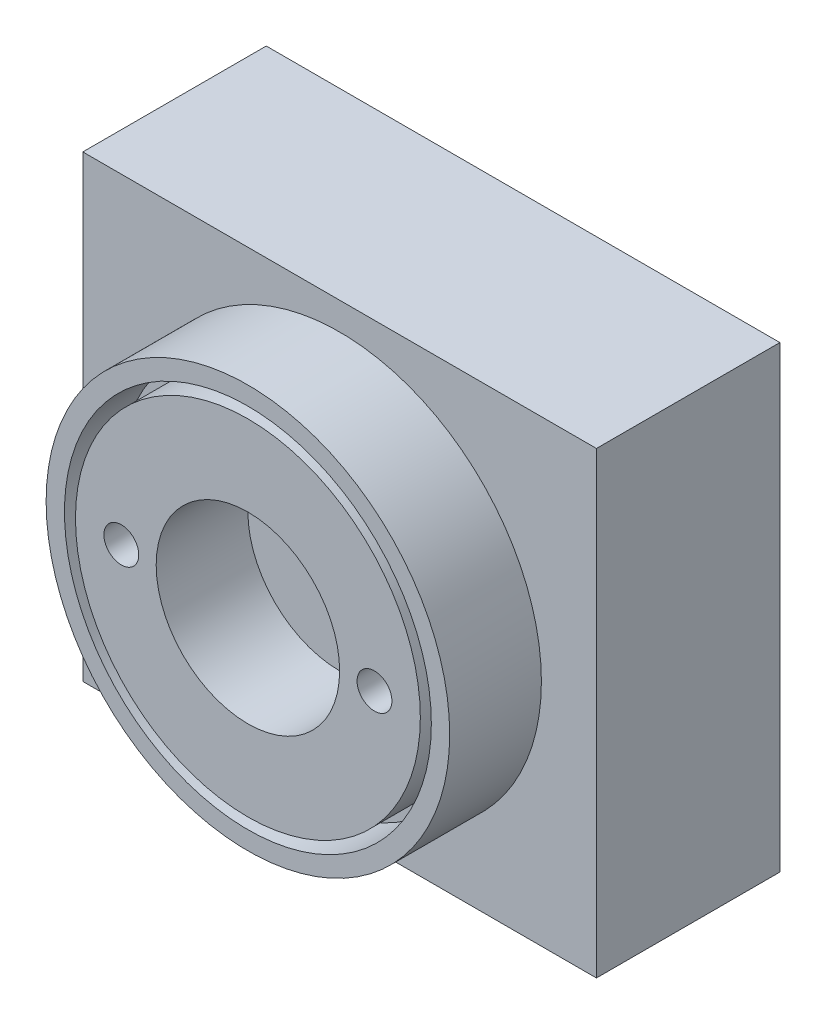
SolidWorks part; units mm, degrees
ref_plane "Front Plane" through (0, 0, 0) normal (0, 0, 1) x (1, 0, 0)
ref_plane "Top Plane" through (0, 0, 0) normal (0, 1, 0) x (1, 0, 0)
ref_plane "Right Plane" through (0, 0, 0) normal (1, 0, 0) x (0, 0, -1)
sketch "Sketch1" plane through (0, 0, 0) normal (0, 0, 1) x (1, 0, 0)
  circle A0 centre (0, 0) radius 55
  circle A1 centre (0, 0) radius 25
  dimension "D1" = 110
  dimension "D2" = 50
extrude "Boss-Extrude1" add sketch "Sketch1" along normal blind 10 and the other way blind 15
sketch "Sketch2" plane through (0, 0, 10) normal (0, 0, 1) x (1, 0, 0)
  line L0 (0, -55) -> (0, 55) construction
  circle A0 centre (0, 0) radius 50
  circle A1 centre (0, 0) radius 47
  circle A2 centre (-34.5, 0) radius 4.75
  circle A3 centre (34.5, 0) radius 4.75
  dimension "D1" = 100
  dimension "D2" = 94
  dimension "D3" = 9.5
  dimension "D4" = 34.5
extrude "Cut-Extrude1" cut sketch "Sketch2" against normal blind 15 contours A3 | A2 | A0 A1
sketch "Sketch4" plane through (0, 0, -15) normal (0, 0, -1) x (-1, 0, 0)
  line L1 (-70, -62.5) -> (70, -62.5)
  line L2 (-70, -62.5) -> (-70, 62.5)
  line L3 (-70, 62.5) -> (70, 62.5)
  line L4 (70, -62.5) -> (70, 62.5)
  line L5 (-70, -62.5) -> (70, 62.5) construction
  line L6 (-70, 62.5) -> (70, -62.5) construction
  point P0 (0, 0)
  dimension "D1" = 125
  dimension "D2" = 140
extrude "Boss-Extrude3" add sketch "Sketch4" along normal blind 50
